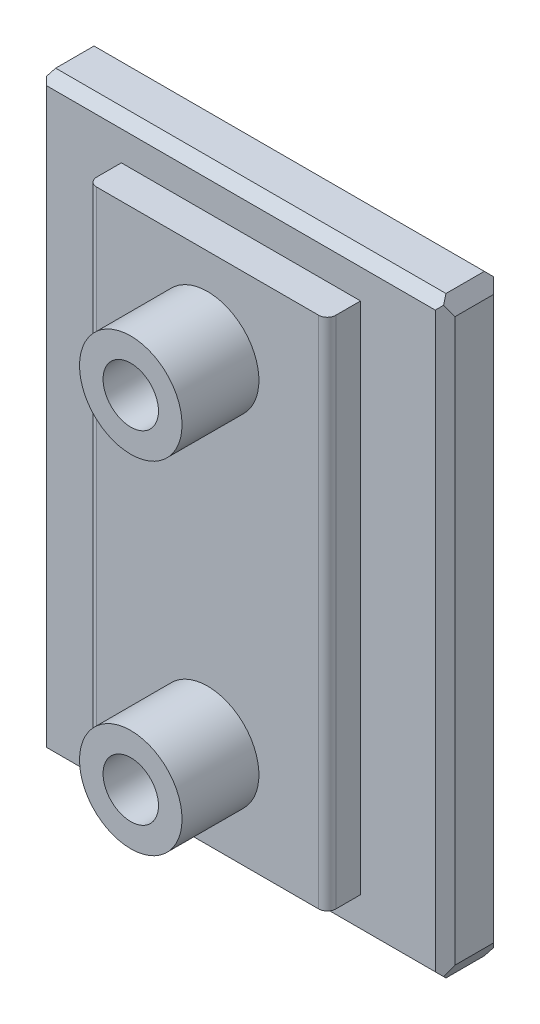
SolidWorks part; units mm, degrees
ref_plane "Front" through (0, 0, 0) normal (0, 0, 1) x (1, 0, 0)
ref_plane "Top" through (0, 0, 0) normal (0, 1, 0) x (1, 0, 0)
ref_plane "Right" through (0, 0, 0) normal (1, 0, 0) x (0, 0, -1)
sketch "Sketch1" plane through (0, 0, 0) normal (0, 0, 1) x (1, 0, 0)
  line L0 (-11.95, -17.35) -> (11.95, -17.35)
  line L1 (11.95, -17.35) -> (11.95, 17.35)
  line L2 (11.95, 17.35) -> (-11.95, 17.35)
  line L3 (-11.95, 17.35) -> (-11.95, -17.35)
  point P4 (0, 17.35)
  point P6 (-11.95, 0)
  dimension "D1" = 23.9
  dimension "D2" = 34.7
extrude "Boss-Extrude1" add sketch "Sketch1" against normal blind 3.4
sketch "Sketch2" plane through (0, 0, 0) normal (0, 0, 1) x (1, 0, 0)
  line L0 (-7, 15.05) -> (7, 15.05)
  line L1 (7, 15.05) -> (7, -15.05)
  line L2 (7, -15.05) -> (-7, -15.05)
  line L3 (-7, -15.05) -> (-7, 15.05)
  point P4 (0, 15.05)
  point P6 (-7, 0)
  dimension "D1" = 14
  dimension "D2" = 30.1
extrude "Boss-Extrude2" add sketch "Sketch2" along normal blind 1.95
sketch "Sketch3" plane through (0, 0, 1.95) normal (0, 0, 1) x (1, 0, 0)
  line L0 (0, 10) -> (0, -10) construction
  circle A0 centre (0, 10) radius 3
  circle A1 centre (0, -10) radius 3
  dimension "D1" = 6
  dimension "D2" = 20
extrude "Boss-Extrude3" add sketch "Sketch3" along normal blind 4.5
chamfer "Chamfer1" distance 0.577 angle 45 4 edges at (0, 17.35, -3.4) (11.95, 0, -3.4) (-11.95, 0, -3.4) (0, -17.35, -3.4)
ref_plane "Plane2" through (5.2, 0, 0) normal (1, 0, 0) x (0, 0, -1)
sketch "Sketch5" plane through (0, 0, 0) normal (1, 0, 0) x (0, 0, -1)
  line L0 (3.4, 16.773) -> (2.823, 17.35)
  line L1 (2.823, 17.35) -> (2.823, 16.827)
  line L2 (2.823, 16.827) -> (2.45, 16.827)
  line L3 (2.45, 16.827) -> (2.45, -16.827)
  line L4 (2.45, -16.827) -> (2.823, -16.827)
  line L5 (2.823, -16.827) -> (2.823, -17.35)
  line L6 (2.823, -17.35) -> (3.4, -16.773)
  line L7 (3.4, -16.773) -> (3.4, 16.773)
  line L8 (0, 0) -> (10.3025, 0) construction
  dimension "D1" = 0.95
  dimension "D2" = 0.523
extrude "Cut-Extrude1" cut sketch "Sketch5" against normal mid plane 10.4
sketch "Sketch6" plane through (0, 0, -2.45) normal (0, 0, -1) x (-1, 0, 0)
  line L0 (-7, 15) -> (-7, -15)
  line L1 (-7, -15) -> (7, -15)
  line L2 (7, -15) -> (7, 15)
  line L3 (7, 15) -> (-7, 15)
  point P4 (-7, 0)
  point P6 (0, -15)
  dimension "D1" = 30
  dimension "D2" = 14
extrude "Cut-Extrude2" cut sketch "Sketch6" against normal blind 0.6
ref_plane "Plane3" through (0, 0, 8) normal (0, 0, 1) x (1, 0, 0)
sketch "Sketch7" plane through (0, 0, -1.85) normal (0, 0, 1) x (1, 0, 0)
  circle A0 centre (0, 10) radius 4.25
  circle A1 centre (0, -10) radius 4.25
extrude "Cut-Extrude3" cut sketch "Sketch7" along normal blind 2.3
sketch "Sketch8" plane through (0, 0, 0.45) normal (0, 0, 1) x (1, 0, 0)
  circle A0 centre (0, 10) radius 2.25
  circle A1 centre (0, -10) radius 2.25
extrude "Cut-Extrude4" cut sketch "Sketch8" along normal blind 1.5
fillet "Fillet1" radius 0.5 2 edges at (7, 0, 1.95) (-7, 0, 1.95)
chamfer "Chamfer2" distance 0.577 angle 45 4 edges at (0, 17.35, 0) (-11.95, 0, 0) (11.95, 0, 0) (0, -17.35, 0)
chamfer "Chamfer3" distance 0.527 angle 60.015 2 edges at (-11.95, -17.35, -1.7) (11.95, 17.35, -1.7)
chamfer "Chamfer4" distance 0.9133 angle 29.985 2 edges at (-11.95, 17.35, -1.7) (11.95, -17.35, -1.7)
sketch "Sketch9" plane through (0, 0, 6.45) normal (0, 0, 1) x (1, 0, 0)
  circle A0 centre (0, 10) radius 1.621
  circle A1 centre (0, -10) radius 1.621
  circle A2 centre (0, -10) radius 3 construction
  circle A3 centre (0, 10) radius 3 construction
  dimension "D1" = 3.242
extrude "Cut-Extrude5" cut sketch "Sketch9" against normal up to next
chamfer "Chamfer5" distance 0.2 angle 45 2 edges at (-2.25, 10, 0.45) (-2.25, -10, 0.45)
